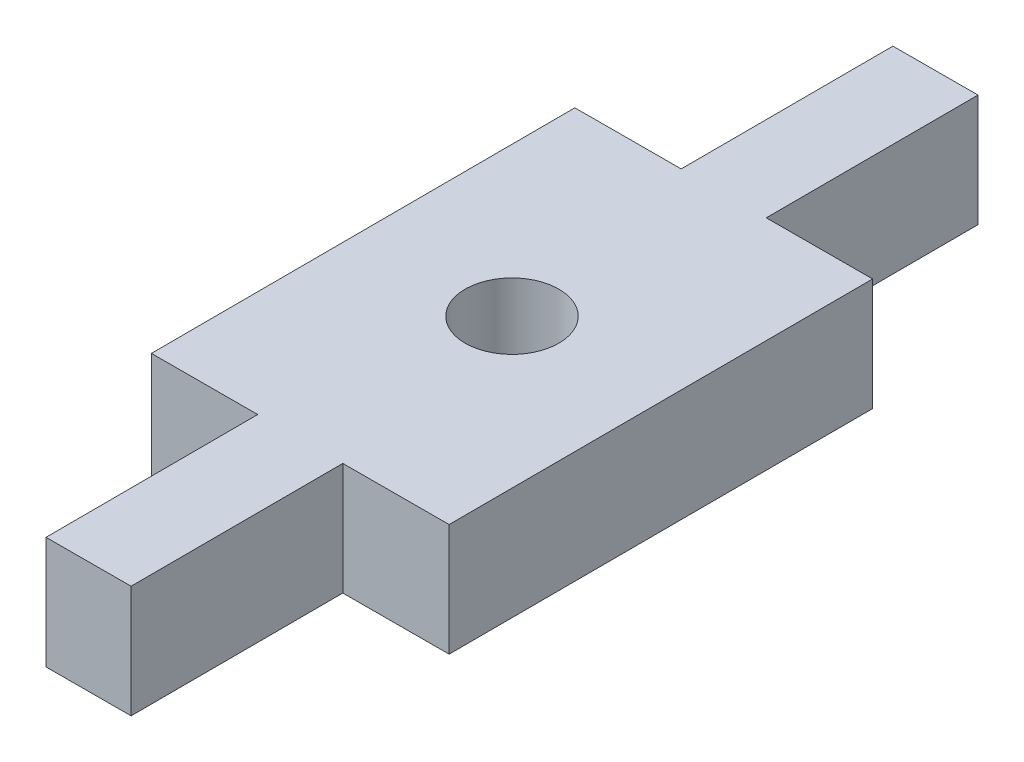
SolidWorks part; units mm, degrees
ref_plane "Front Plane" through (0, 0, 0) normal (0, 0, 1) x (1, 0, 0)
ref_plane "Top Plane" through (0, 0, 0) normal (0, 1, 0) x (1, 0, 0)
ref_plane "Right Plane" through (0, 0, 0) normal (1, 0, 0) x (0, 0, -1)
sketch "Sketch1" plane through (0, 0, 0) normal (0, 1, 0) x (1, 0, 0)
  line L0 (95.6752, 121.5443) -> (97.5532, 119.6748) construction
  line L1 (97.5489, 121.5485) -> (95.6795, 119.6705) construction
  line L75 (95.4277, 114.6068) -> (95.4414, 108.6069)
  line L76 (95.4414, 108.6069) -> (97.8414, 108.6123)
  line L77 (97.8414, 108.6123) -> (97.8278, 114.6122)
  line L78 (97.8278, 114.6122) -> (100.8277, 114.619)
  line L79 (100.8277, 114.619) -> (100.8007, 126.619)
  line L80 (100.8007, 126.619) -> (97.8008, 126.6122)
  line L81 (97.8008, 126.6122) -> (97.7874, 132.6122)
  line L82 (97.7874, 132.6122) -> (95.3874, 132.6068)
  line L83 (95.3874, 132.6068) -> (95.4008, 126.6068)
  line L84 (95.4008, 126.6068) -> (92.4007, 126.6002)
  line L85 (92.4007, 126.6002) -> (92.4277, 114.6002)
  line L86 (92.4277, 114.6002) -> (95.4277, 114.6068)
  circle A0 centre (96.6142, 120.6096) radius 1.3249
  dimension "D1" = 8.4
  dimension "D2" = 4.2
  dimension "D3" = 12
  dimension "D4" = 12
  dimension "D5" = 12
  dimension "D6" = 12
  dimension "D7" = 2.4
  dimension "D8" = 2.4
  dimension "D9" = 1.2
  dimension "D10" = 1.2
extrude "Boss-Extrude1" add sketch "Sketch1" along normal blind 3.175
